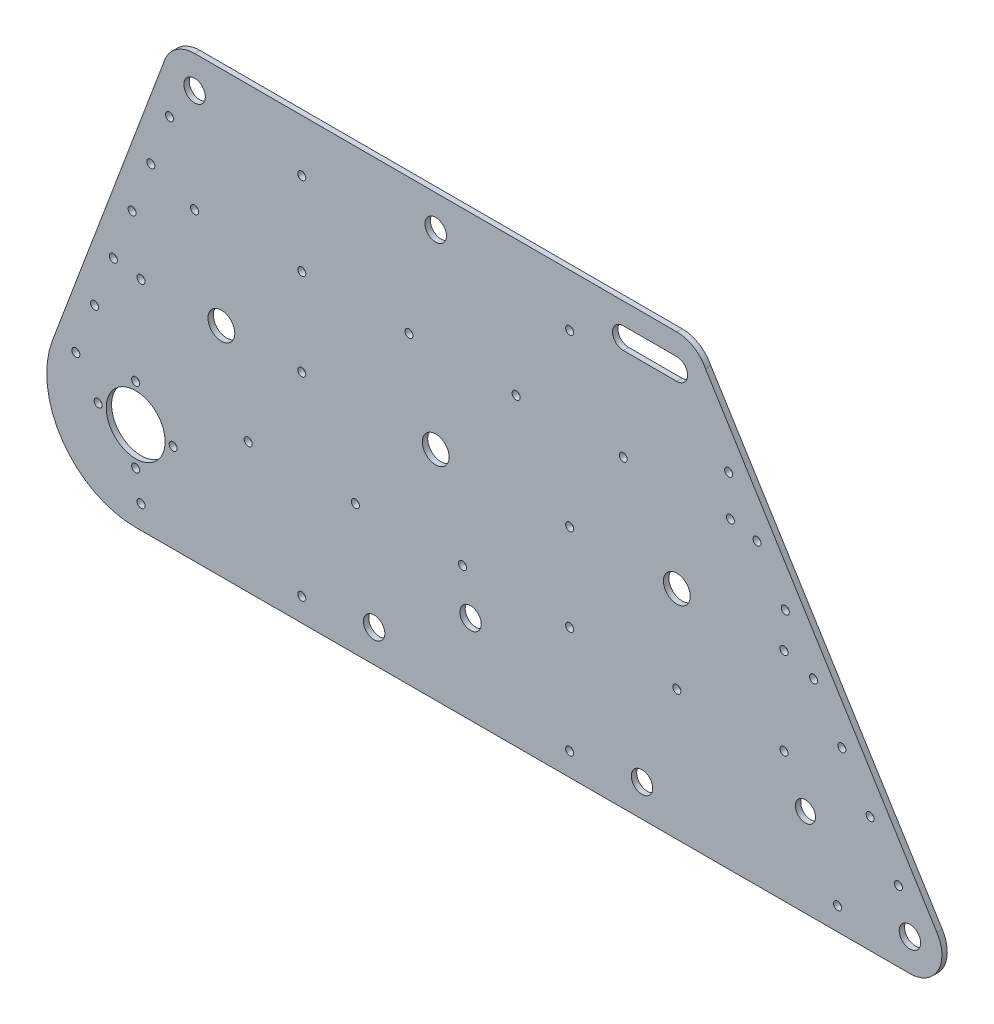
SolidWorks part; units mm, degrees
ref_plane "Front Plane" through (0, 0, 0) normal (0, 0, 1) x (1, 0, 0)
ref_plane "Top Plane" through (0, 0, 0) normal (0, 1, 0) x (1, 0, 0)
ref_plane "Right Plane" through (0, 0, 0) normal (1, 0, 0) x (0, 0, -1)
sketch "Sketch1" plane through (0, 0, 0) normal (0, 0, 1) x (1, 0, 0)
  line B0 (-105.2394, 83.4869) -> (-147.4084, -28.8454)
  ellipse B1 centre (-94.3313, 78.4869) end of major axis (-94.3313, 66.4869) minor radius 11.9994 (-94.3313, 90.4869) -> (-105.2394, 83.4869) ccw
  ellipse B2 centre (-94.3313, 78.4869) end of major axis (-94.3313, 74.4869) minor radius 3.9998
  ellipse B3 centre (-4.3358, 78.4869) end of major axis (-4.3358, 74.4869) minor radius 3.9998
  line B4 (85.6597, 74.4869) -> (65.6607, 74.4869)
  ellipse B5 centre (-103.6719, 65.3682) end of major axis (-103.6719, 66.8682) minor radius 1.4999
  ellipse B6 centre (-110.67, 46.6324) end of major axis (-110.67, 48.1324) minor radius 1.4999
  ellipse B7 centre (-94.3313, 39.9869) end of major axis (-94.3313, 38.4869) minor radius 1.4999
  ellipse B8 centre (-117.6679, 27.8973) end of major axis (-117.6679, 29.3973) minor radius 1.4999
  ellipse B9 centre (-114.3303, 7.4869) end of major axis (-114.3303, 5.9869) minor radius 1.4999
  ellipse B10 centre (-124.6658, 9.1621) end of major axis (-124.6658, 10.6621) minor radius 1.4999
  ellipse B11 centre (-131.6638, -9.5733) end of major axis (-131.6638, -11.0733) minor radius 1.4999
  ellipse B12 centre (-116.3302, -40.5131) end of major axis (-116.3302, -51.5131) minor radius 10.9995
  ellipse B13 centre (-116.3302, -26.5131) end of major axis (-116.3302, -28.0131) minor radius 1.4999
  ellipse B14 centre (-138.6618, -28.3089) end of major axis (-138.6618, -26.8089) minor radius 1.4999
  ellipse B15 centre (-130.3295, -40.5131) end of major axis (-130.3295, -42.0131) minor radius 1.4999
  ellipse B16 centre (-102.3309, -40.5131) end of major axis (-102.3309, -42.0131) minor radius 1.4999
  ellipse B17 centre (-116.3302, -54.5131) end of major axis (-116.3302, -56.0131) minor radius 1.4999
  ellipse B18 centre (-114.3303, -65.0131) end of major axis (-114.3303, -66.5131) minor radius 1.4999
  line B19 (172.6659, -73.4567) -> (-116.3024, -73.7108)
  ellipse B20 centre (-54.3333, -65.0131) end of major axis (-54.3333, -66.5131) minor radius 1.4999
  ellipse B21 centre (-27.3345, -61.5131) end of major axis (-27.3345, -65.5131) minor radius 3.9998
  ellipse B22 centre (-74.3323, -25.0131) end of major axis (-74.3323, -26.5131) minor radius 1.4999
  ellipse B23 centre (-84.3318, 7.4869) end of major axis (-84.3318, 2.4869) minor radius 4.9998
  ellipse B24 centre (-34.3343, -25.0131) end of major axis (-34.3343, -26.5131) minor radius 1.4999
  ellipse B25 centre (-54.3333, 39.9869) end of major axis (-54.3333, 38.4869) minor radius 1.4999
  ellipse B26 centre (-4.3358, 7.4869) end of major axis (-4.3358, 2.4869) minor radius 4.9997
  ellipse B27 centre (-14.3353, 39.9869) end of major axis (-14.3353, 38.4869) minor radius 1.4999
  ellipse B28 centre (5.6637, -25.0131) end of major axis (5.6637, -26.5131) minor radius 1.4999
  ellipse B29 centre (8.6636, -40.5131) end of major axis (8.6636, -44.5131) minor radius 3.9998
  ellipse B30 centre (45.6617, -25.0131) end of major axis (45.6617, -26.5131) minor radius 1.4999
  ellipse B31 centre (45.6617, 7.4869) end of major axis (45.6617, 5.9869) minor radius 1.4999
  ellipse B32 centre (25.6627, 39.9869) end of major axis (25.6627, 38.4869) minor radius 1.4999
  ellipse B33 centre (45.6617, 70.9869) end of major axis (45.6617, 69.4869) minor radius 1.4999
  ellipse B34 centre (65.6607, 39.9869) end of major axis (65.6607, 38.4869) minor radius 1.4999
  ellipse B35 centre (133.6573, -40.5131) end of major axis (133.6573, -44.2631) minor radius 3.7498
  ellipse B36 centre (72.6604, -61.5131) end of major axis (72.6604, -65.5131) minor radius 3.9998
  ellipse B37 centre (85.6597, -25.0131) end of major axis (85.6597, -26.5131) minor radius 1.4999
  ellipse B38 centre (45.6617, -65.0131) end of major axis (45.6617, -66.5131) minor radius 1.4999
  ellipse B39 centre (125.6577, -25.0131) end of major axis (125.6577, -26.5131) minor radius 1.4999
  ellipse B40 centre (145.6567, -65.0131) end of major axis (145.6567, -66.5131) minor radius 1.4999
  ellipse B41 centre (172.6554, -61.5131) end of major axis (172.6554, -73.4567) minor radius 11.943 (172.6659, -73.4567) -> (182.7461, -55.1244) ccw
  ellipse B42 centre (168.3499, -47.1115) end of major axis (168.3499, -48.6115) minor radius 1.4999
  ellipse B43 centre (157.7954, -30.1237) end of major axis (157.7954, -31.6237) minor radius 1.4999
  ellipse B44 centre (147.241, -13.1361) end of major axis (147.241, -14.6361) minor radius 1.4999
  ellipse B45 centre (136.6861, 3.8522) end of major axis (136.6861, 2.3522) minor radius 1.4999
  ellipse B46 centre (125.6577, 7.4869) end of major axis (125.6577, 5.9869) minor radius 1.4999
  ellipse B47 centre (85.6597, 7.4869) end of major axis (85.6597, 2.4869) minor radius 4.9997
  ellipse B48 centre (126.1314, 20.8403) end of major axis (126.1314, 19.3403) minor radius 1.4999
  ellipse B49 centre (115.5769, 37.8281) end of major axis (115.5769, 36.3281) minor radius 1.4999
  ellipse B50 centre (105.6587, 39.9869) end of major axis (105.6587, 38.4869) minor radius 1.4999
  line B51 (96.3607, 83.9155) -> (182.7461, -55.1244)
  ellipse B52 centre (105.0226, 54.8156) end of major axis (105.0226, 53.3156) minor radius 1.4999
  line B53 (-94.3313, 90.4869) -> (85.6597, 90.4869)
  line B54 (65.6607, 82.4869) -> (85.6597, 82.4869)
  ellipse B55 centre (65.6607, 78.4869) end of major axis (65.6607, 74.4869) minor radius 3.9998 (65.6607, 82.4869) -> (65.6607, 74.4869) ccw
  ellipse B56 centre (85.6597, 78.4869) end of major axis (85.6597, 74.4869) minor radius 3.9998 (85.6597, 74.4869) -> (85.6597, 82.4869) ccw
  ellipse B57 centre (-116.3302, -40.5131) end of major axis (-116.3302, -73.7108) minor radius 33.196 (-147.4084, -28.8454) -> (-116.301, -73.7108) ccw
  ellipse B58 centre (85.6597, 78.4869) end of major axis (85.6597, 66.4869) minor radius 11.9994 (96.3626, 83.9124) -> (85.6597, 90.4869) ccw
sketch_block_instance "BodyOutline-1"
sketch_block "Block1"
sketch "Sketch2" plane through (0, 0, 0) normal (0, 0, 1) x (1, 0, 0)
  line L0 (65.6607, 82.4869) -> (85.6597, 82.4869)
  line L1 (85.6597, 74.4869) -> (65.6607, 74.4869)
  line L2 (96.3626, 83.9124) -> (182.7461, -55.1244)
  line L4 (172.6658, -73.4563) -> (-116.3011, -73.7093)
  line L6 (-147.4084, -28.8454) -> (-105.2394, 83.4869)
  line L7 (-94.3313, 90.4864) -> (85.6387, 90.4864)
  circle A0 centre (-94.3313, 78.4869) radius 3.9998
  circle A1 centre (-4.3358, 78.4869) radius 3.9998
  circle A2 centre (-54.3333, 70.9869) radius 1.4999
  circle A3 centre (-103.6719, 65.3682) radius 1.4999
  circle A4 centre (-110.67, 46.6324) radius 1.4999
  circle A5 centre (-94.3313, 39.9869) radius 1.4999
  circle A6 centre (-117.6679, 27.8973) radius 1.4999
  circle A7 centre (-114.3303, 7.4869) radius 1.4999
  circle A8 centre (-124.6658, 9.1621) radius 1.4999
  circle A9 centre (-131.6638, -9.5733) radius 1.4999
  circle A10 centre (-116.3302, -26.5131) radius 1.4999
  circle A11 centre (-138.6618, -28.3089) radius 1.4999
  circle A12 centre (-130.3295, -40.5131) radius 1.4999
  circle A13 centre (-102.3309, -40.5131) radius 1.4999
  circle A14 centre (-114.3303, -65.0131) radius 1.4999
  circle A15 centre (-116.3302, -54.5131) radius 1.4999
  circle A16 centre (8.6636, -40.5131) radius 3.9998
  circle A17 centre (-54.3333, -65.0131) radius 1.4999
  circle A18 centre (-27.3345, -61.5131) radius 3.9998
  circle A19 centre (-74.3323, -25.0131) radius 1.4999
  circle A20 centre (-84.3318, 7.4869) radius 4.9998
  circle A21 centre (-54.3333, 7.4869) radius 1.4999
  circle A22 centre (-34.3343, -25.0131) radius 1.4999
  circle A23 centre (-54.3333, 39.9869) radius 1.4999
  circle A24 centre (-14.3353, 39.9869) radius 1.4999
  circle A25 centre (-4.3358, 7.4869) radius 4.9997
  circle A26 centre (5.6637, -25.0131) radius 1.4999
  circle A27 centre (85.6597, -25.0131) radius 1.4999
  circle A28 centre (45.6617, -25.0131) radius 1.4999
  circle A29 centre (45.6617, 7.4869) radius 1.4999
  circle A30 centre (25.6627, 39.9869) radius 1.4999
  circle A31 centre (45.6617, 70.9869) radius 1.4999
  circle A32 centre (65.6607, 39.9869) radius 1.4999
  arc A33 (-147.4084, -28.8454) -> (-116.3011, -73.7093) centre (-116.3302, -40.5131) ccw
  circle A34 centre (72.6604, -61.5131) radius 3.9998
  circle A35 centre (45.6617, -65.0131) radius 1.4999
  circle A36 centre (125.6577, -25.0131) radius 1.4999
  circle A37 centre (133.6573, -40.5131) radius 3.7498
  circle A38 centre (145.6567, -65.0131) radius 1.4999
  circle A39 centre (172.6554, -61.5131) radius 3.9998
  circle A40 centre (168.3499, -47.1115) radius 1.4999
  circle A41 centre (157.7954, -30.1237) radius 1.4999
  circle A42 centre (147.241, -13.1361) radius 1.4999
  circle A43 centre (136.6861, 3.8522) radius 1.4999
  circle A44 centre (125.6577, 7.4869) radius 1.4999
  circle A45 centre (85.6597, 7.4869) radius 4.9997
  circle A46 centre (126.1314, 20.8403) radius 1.4999
  circle A47 centre (115.5769, 37.8281) radius 1.4999
  circle A48 centre (105.6587, 39.9869) radius 1.5
  circle A49 centre (105.0226, 54.8156) radius 1.4999
  circle A50 centre (-116.3302, -40.5131) radius 10.9995
  arc A51 (-105.2394, 83.4869) -> (-94.3313, 90.4864) centre (-94.3313, 78.4869) cw
  arc A52 (96.3626, 83.9124) -> (85.6387, 90.4864) centre (85.6597, 78.4869) ccw
  arc A53 (85.6597, 74.4869) -> (85.6597, 82.4869) centre (85.6597, 78.4869) ccw
  arc A54 (65.6607, 82.4869) -> (65.6607, 74.4869) centre (65.6607, 78.4869) ccw
  arc A55 (182.7461, -55.1244) -> (172.6658, -73.4563) centre (172.6554, -61.5131) cw
  ellipse E0 centre (85.6597, 78.4869) end of major axis (85.6597, 74.4869) minor radius 3.9998 (85.6597, 74.4869) -> (85.6597, 82.4869) ccw construction
  ellipse E2 centre (65.6607, 78.4869) end of major axis (65.6607, 74.4869) minor radius 3.9998 (65.6607, 82.4869) -> (65.6607, 74.4869) ccw construction
extrude "Boss-Extrude1" add sketch "Sketch2" along normal blind 2
